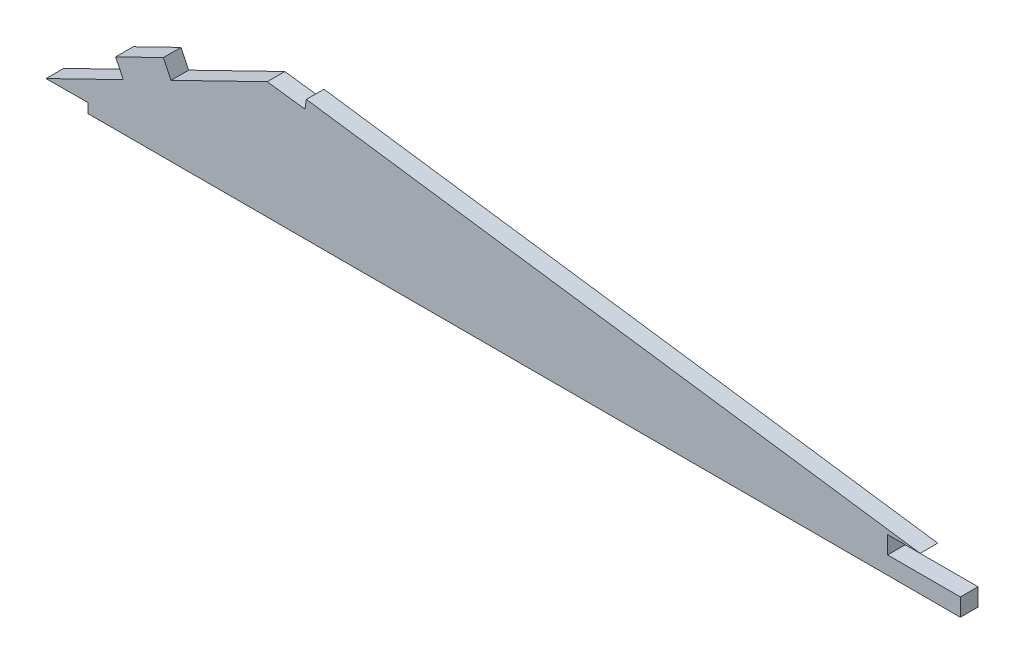
SolidWorks part; units mm, degrees
ref_plane "前视基准面" through (0, 0, 0) normal (0, 0, 1) x (1, 0, 0)
ref_plane "上视基准面" through (0, 0, 0) normal (0, 1, 0) x (1, 0, 0)
ref_plane "右视基准面" through (0, 0, 0) normal (1, 0, 0) x (0, 0, -1)
sketch "Model" plane through (0, 0, 0) normal (0, 0, 1) x (1, 0, 0)
  line L0 (16.7213, 12.8223) -> (27.6289, 18.1423)
  line L1 (11.3026, 10.1795) -> (10.4259, 11.977)
  line L2 (10.4259, 11.977) -> (15.8445, 14.6199)
  line L3 (15.8445, 14.6199) -> (16.7213, 12.8223)
  line L4 (2.529, 5.9003) -> (11.3026, 10.1795)
  line L5 (7.3146, 4.8356) -> (106.2916, 4.8356)
  line L6 (32.0713, 18.6245) -> (101.7229, 8.8356)
  line L7 (27.6289, 18.1423) -> (31.9231, 17.5868)
  line L8 (31.9231, 17.5868) -> (32.0713, 18.6245)
  line L9 (7.3146, 4.8356) -> (7.3104, 5.9188)
  line L10 (7.3104, 5.9188) -> (2.529, 5.9003)
  line L11 (98.0354, 6.8356) -> (106.2916, 6.8356)
  line L12 (98.0354, 8.8356) -> (101.7229, 8.8356)
  line L13 (98.0354, 6.8356) -> (98.0354, 8.8356)
  line L14 (106.2916, 4.8356) -> (106.2916, 6.8356)
  point P16 (32.0713, 18.6271)
extrude "凸台-拉伸1" add sketch "Model" along normal blind 2
